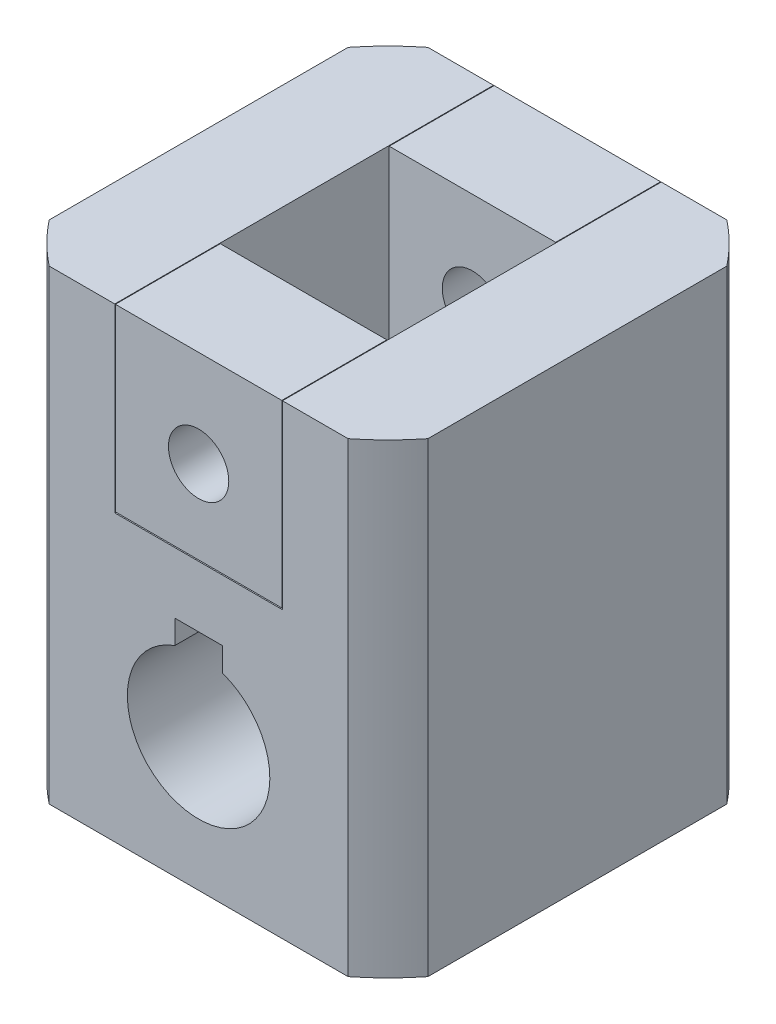
SolidWorks part; units mm, degrees
material "AISI 1045 Steel, cold drawn"
ref_plane "Frontal Plane" through (0, 0, 0) normal (0, 0, 1) x (1, 0, 0)
ref_plane "Horizontal Plane" through (0, 0, 0) normal (0, 1, 0) x (1, 0, 0)
ref_plane "Profile Plane" through (0, 0, 0) normal (1, 0, 0) x (0, 0, -1)
sketch "Sketch1" plane through (0, 0, 0) normal (0, 1, 0) x (1, 0, 0)
  line L1 (-19.939, -19.939) -> (19.939, -19.939)
  line L2 (-19.939, -19.939) -> (-19.939, 19.939)
  line L3 (-19.939, 19.939) -> (19.939, 19.939)
  line L4 (19.939, -19.939) -> (19.939, 19.939)
  line L5 (-19.939, -19.939) -> (19.939, 19.939) construction
  line L6 (-19.939, 19.939) -> (19.939, -19.939) construction
  point P0 (0, 0)
  dimension "D1" = 39.878
  dimension "D2" = 39.878
extrude "Boss-Extrude1" add sketch "Sketch1" along normal blind 49.05
sketch "Sketch2" plane through (0, 49.05, 0) normal (0, -1, 0) x (1, 0, 0)
  line L0 (19.939, -19.939) -> (-19.939, -19.939) construction
  line L1 (-8.8265, 19.939) -> (8.8265, 19.939)
  line L2 (-8.8265, 19.939) -> (-8.8265, -19.939)
  line L3 (-8.8265, -19.939) -> (8.8265, -19.939)
  line L4 (8.8265, 19.939) -> (8.8265, -19.939)
  line L5 (-8.8265, 19.939) -> (8.8265, -19.939) construction
  line L6 (-8.8265, -19.939) -> (8.8265, 19.939) construction
  point P0 (0, 0)
  dimension "D1" = 17.653
extrude "Cut-Extrude1" cut sketch "Sketch2" along normal blind 19.05
sketch "Sketch4" plane through (0, 49.05, 0) normal (0, 1, 0) x (1, 0, 0)
  circle A0 centre (0, 0) radius 25.4
  circle A1 centre (0, 0) radius 30.48
  dimension "D1" = 50.8
  dimension "D2" = 5.08
extrude "Cut-Extrude3" cut sketch "Sketch4" against normal through all
sketch "Sketch5" plane through (19.939, 0, 0) normal (1, 0, 0) x (0, 0, -1)
  line L0 (-15.7352, 49.05) -> (15.7352, 49.05) construction
  line L1 (-2.5, 21.0691) -> (-2.5, 23.5691)
  line L2 (-2.5, 23.5691) -> (2.5, 23.5691)
  line L3 (2.5, 23.5691) -> (2.5, 21.0691)
  circle A1 centre (0, 38.89) radius 3.175
  arc A2 (2.5, 21.0691) -> (-2.5, 21.0691) centre (0, 13.998) cw
  dimension "D1" = 7.5
  dimension "D3" = 6.35
  dimension "D2" = 5
  dimension "D4" = 10.16
  dimension "D5" = 2.5
  dimension "D6" = 35.052
extrude "Cut-Extrude4" [suppressed] cut sketch "Sketch5" against normal through all
sketch "Sketch6" plane through (0, 0, 19.939) normal (0, 0, 1) x (1, 0, 0)
  line L0 (-2.5, 21.0691) -> (-2.5, 23.5691)
  line L1 (-2.5, 23.5691) -> (2.5, 23.5691)
  line L2 (2.5, 23.5691) -> (2.5, 21.0691)
  line L3 (-15.7352, 49.05) -> (-8.8265, 49.05) construction
  arc A0 (2.5, 21.0691) -> (-2.5, 21.0691) centre (0, 13.998) cw
  dimension "D3" = 7.5
  dimension "D2" = 2.5
  dimension "D4" = 5
  dimension "D5" = 35.052
extrude "Cut-Extrude5" cut sketch "Sketch6" against normal through all
sketch "Sketch7" plane through (0, 49.05, 0) normal (0, 1, 0) x (1, 0, 0)
  line L0 (-8.763, -19.939) -> (8.763, -19.939)
  line L1 (8.763, -19.939) -> (8.763, -8.89)
  line L2 (8.763, -8.89) -> (-8.763, -8.89)
  line L3 (-8.763, -8.89) -> (-8.763, -19.939)
  line L5 (8.8265, -19.939) -> (-8.8265, -19.939) construction
  line L6 (-8.8265, 0) -> (8.8265, 0) construction
  line L7 (-8.8265, -19.939) -> (-8.8265, 19.939) construction
  line L8 (8.8265, 19.939) -> (8.8265, -19.939) construction
  line L9 (8.763, 8.89) -> (-8.763, 8.89)
  line L10 (8.763, 19.939) -> (8.763, 8.89)
  line L11 (-8.763, 19.939) -> (8.763, 19.939)
  line L12 (-8.763, 8.89) -> (-8.763, 19.939)
  point P2 (0, -8.89)
  dimension "D1" = 17.526
  dimension "D2" = 11.049
extrude "Boss-Extrude2" add sketch "Sketch7" against normal offset from surface (18.923 mm away) 0.127 up to face at (0, 30, 0)
sketch "Sketch8" plane through (0, 0, 19.939) normal (0, 0, 1) x (1, 0, 0)
  line L0 (-8.763, 49.05) -> (8.763, 49.05) construction
  circle A0 centre (0, 38.89) radius 3.175
  dimension "D1" = 6.35
  dimension "D2" = 10.16
extrude "Cut-Extrude6" cut sketch "Sketch8" against normal through all
sketch "Sketch9" plane through (-19.939, 0, 0) normal (1, 0, 0) x (0, 0, -1)
  line L0 (-15.7352, 49.05) -> (15.7352, 49.05) construction
  circle A0 centre (0, 42.7) radius 2.1
  circle A1 centre (0, 30) radius 2.1
  dimension "D1" = 4.2
  dimension "D2" = 12.7
  dimension "D3" = 6.35
extrude "Cut-Extrude7" cut sketch "Sketch9" along normal offset from surface (6.0325 mm away) 5.08 up to face at (-8.8265, 39.525, 0)
